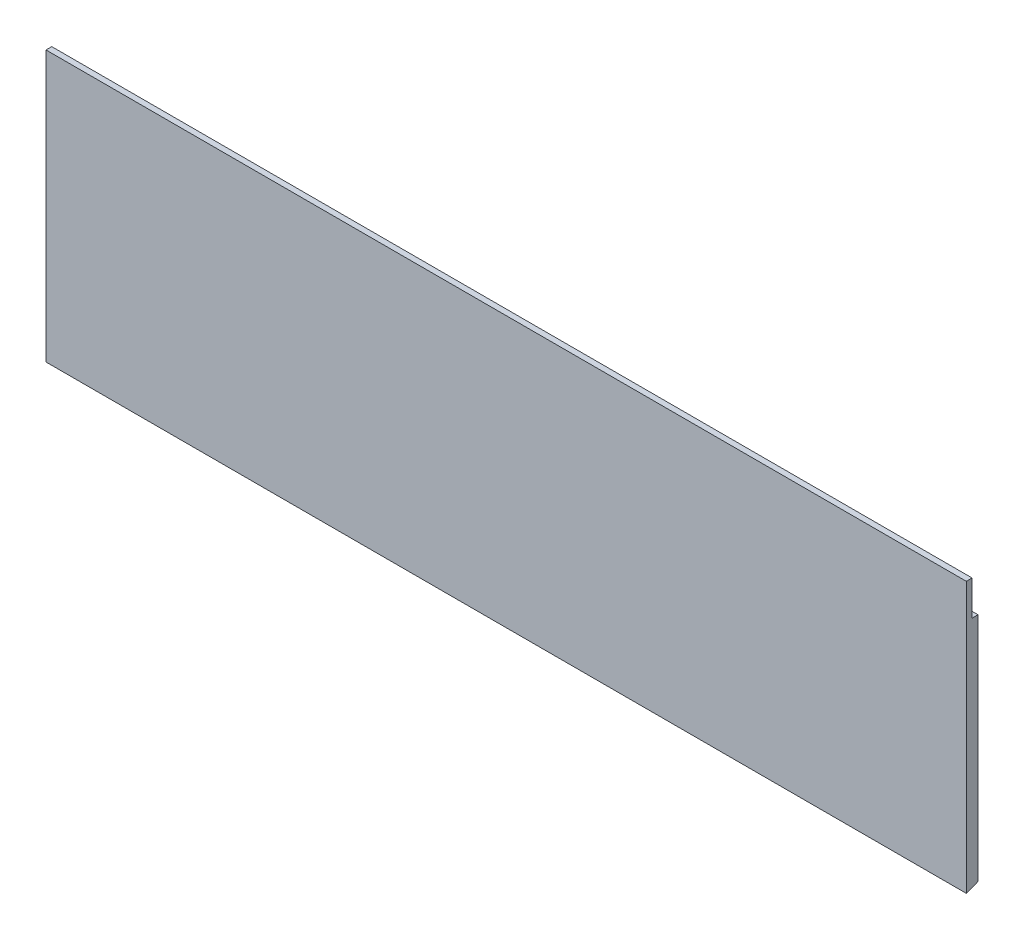
SolidWorks part; units mm, degrees
ref_plane "Front Plane" through (0, 0, 0) normal (0, 0, 1) x (1, 0, 0)
ref_plane "Top Plane" through (0, 0, 0) normal (0, 1, 0) x (1, 0, 0)
ref_plane "Right Plane" through (0, 0, 0) normal (1, 0, 0) x (0, 0, -1)
sketch "Sketch1" plane through (0, 0, 0) normal (0, 0, 1) x (1, 0, 0)
  line L0 (-631, 185.31) -> (-631, -185.31)
  line L1 (-631, -185.31) -> (631, -185.31) construction
  line L2 (-631, -185.31) -> (-631, 185.31) construction
  line L3 (-631, 185.31) -> (631, 185.31) construction
  line L4 (631, -185.31) -> (631, 185.31) construction
  line L5 (-631, -185.31) -> (631, 185.31) construction
  line L6 (-631, 185.31) -> (631, -185.31) construction
  line L7 (-631, -185.31) -> (631, -185.31)
  line L8 (631, -185.31) -> (631, 185.31)
  line L9 (631, 185.31) -> (-631, 185.31)
  point P0 (0, 0)
  dimension "D1" = 370.62
  dimension "D2" = 1262
extrude "Boss-Extrude1" add sketch "Sketch1" along normal blind 16
sketch "Sketch2" plane through (0, 0, 0) normal (0, 0, -1) x (-1, 0, 0)
  line L0 (-631, -185.31) -> (-631, 185.31) construction
  line L1 (631, 185.31) -> (-631, 185.31)
  line L2 (631, 185.31) -> (631, 137.61)
  line L3 (631, 137.61) -> (-631, 137.61)
  line L4 (-631, 185.31) -> (-631, 137.61)
  dimension "D1" = 47.7
extrude "Cut-Extrude1" cut sketch "Sketch2" against normal blind 8.1
sketch "Sketch3" plane through (631, 0, 0) normal (1, 0, 0) x (0, 0, -1)
  line L0 (-16, -185.31) -> (0, -179.1682)
  line L1 (0, -185.31) -> (0, 137.61) construction
  line L2 (0, -179.1682) -> (0, -185.31)
  line L3 (0, -185.31) -> (-16, -185.31)
  line L4 (-16, -185.31) -> (-16, 185.31) construction
  dimension "D1" = 69
extrude "Cut-Extrude2" cut sketch "Sketch3" against normal through all
